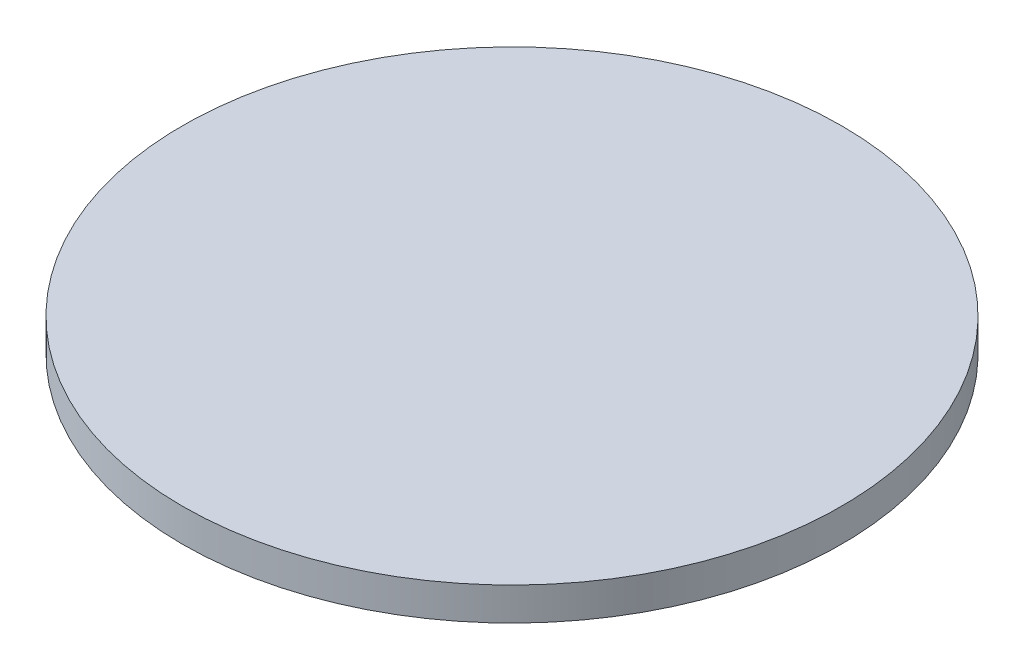
SolidWorks part; units mm, degrees
ref_plane "前视基准面" through (0, 0, 0) normal (0, 0, 1) x (1, 0, 0)
ref_plane "上视基准面" through (0, 0, 0) normal (0, 1, 0) x (1, 0, 0)
ref_plane "右视基准面" through (0, 0, 0) normal (1, 0, 0) x (0, 0, -1)
other "Configuration Table"
sketch "草图1" plane through (0, 0, 0) normal (0, 1, 0) x (1, 0, 0)
  circle A0 centre (0, 0) radius 100
  dimension "D1" = 200
extrude "凸台-拉伸1" add sketch "草图1" along normal blind 10
